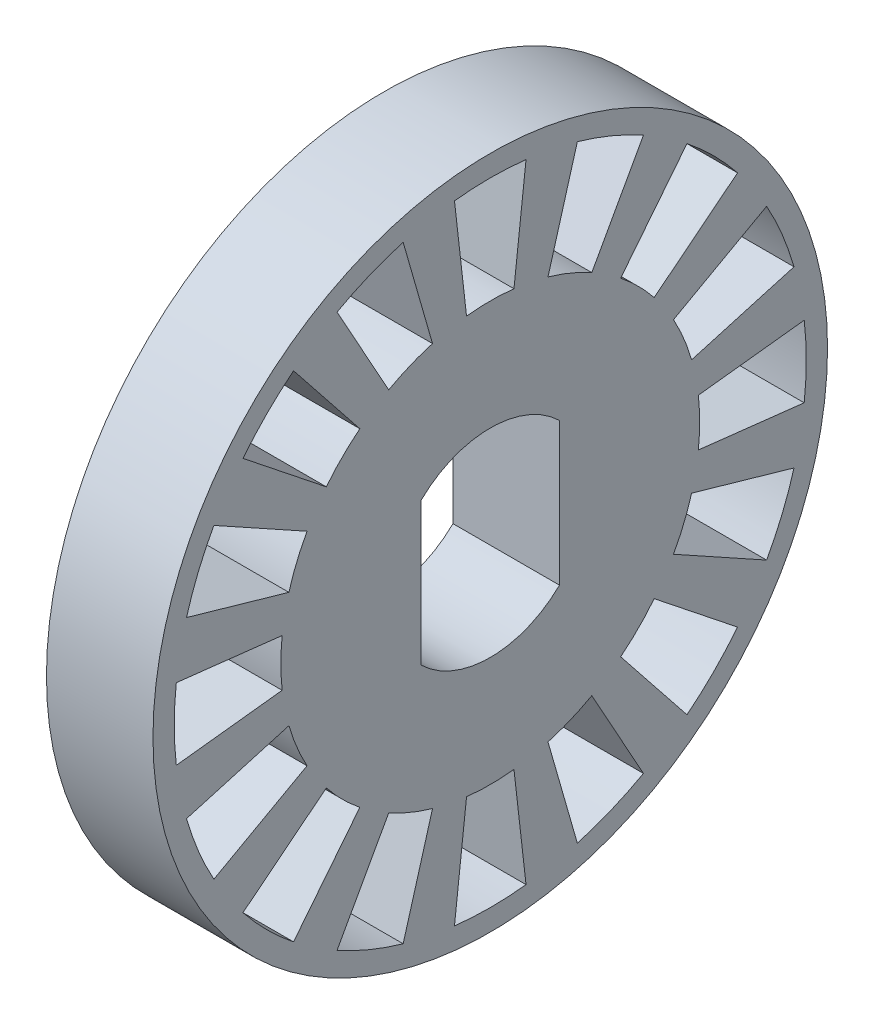
SolidWorks part; units mm, degrees
ref_plane "Front Plane" through (0, 0, 0) normal (0, 0, 1) x (1, 0, 0)
ref_plane "Top Plane" through (0, 0, 0) normal (0, 1, 0) x (1, 0, 0)
ref_plane "Right Plane" through (0, 0, 0) normal (1, 0, 0) x (0, 0, -1)
sketch "Sketch1" plane through (0, 0, 0) normal (1, 0, 0) x (0, 0, -1)
  line L1 (-1.95, -2.0094) -> (1.95, -2.0094) construction
  line L2 (-1.95, -2.0094) -> (-1.95, 2.0094)
  line L3 (-1.95, 2.0094) -> (1.95, 2.0094) construction
  line L4 (1.95, -2.0094) -> (1.95, 2.0094)
  line L5 (-1.95, -2.0094) -> (1.95, 2.0094) construction
  line L6 (-1.95, 2.0094) -> (1.95, -2.0094) construction
  circle A0 centre (0, 0) radius 9.5
  circle A1 centre (0, 0) radius 2.8
  dimension "D1" = 19
  dimension "D2" = 5.6
  dimension "D3" = 3.9
extrude "Boss-Extrude1" add sketch "Sketch1" along normal blind 3 contours A0 A1 | L4 A1 | L2 A1
sketch "Sketch2" [suppressed] plane through (3, 0, 0) normal (1, 0, 0) x (0, 0, -1)
  line L0 (0, 0) -> (0, 9.5) construction
  line L1 (2.8313, 6.1249) -> (3.4493, 8.027)
  line L2 (-0.8, 6.7) -> (0.8, 6.7)
  line L3 (-0.8, 6.7) -> (-0.8, 8.7)
  line L4 (-0.8, 8.7) -> (0.8, 8.7)
  line L5 (0.8, 6.7) -> (0.8, 8.7)
  line L6 (-0.8, 6.7) -> (0.8, 8.7) construction
  line L7 (-0.8, 8.7) -> (0.8, 6.7) construction
  line L8 (1.9276, 8.5214) -> (3.4493, 8.027)
  line L9 (1.3096, 6.6193) -> (1.9276, 8.5214)
  line L10 (1.3096, 6.6193) -> (2.8313, 6.1249)
  line L11 (4.5854, 4.9502) -> (5.7609, 6.5682)
  line L12 (4.4665, 7.5087) -> (5.7609, 6.5682)
  line L13 (3.2909, 5.8906) -> (4.4665, 7.5087)
  line L14 (3.2909, 5.8906) -> (4.5854, 4.9502)
  line L15 (5.8906, 3.2909) -> (7.5087, 4.4665)
  line L16 (6.5682, 5.7609) -> (7.5087, 4.4665)
  line L17 (4.9502, 4.5854) -> (6.5682, 5.7609)
  line L18 (4.9502, 4.5854) -> (5.8906, 3.2909)
  line L19 (6.6193, 1.3096) -> (8.5214, 1.9276)
  line L20 (8.027, 3.4493) -> (8.5214, 1.9276)
  line L21 (6.1249, 2.8313) -> (8.027, 3.4493)
  line L22 (6.1249, 2.8313) -> (6.6193, 1.3096)
  line L23 (6.7, -0.8) -> (8.7, -0.8)
  line L24 (8.7, 0.8) -> (8.7, -0.8)
  line L25 (6.7, 0.8) -> (8.7, 0.8)
  line L26 (6.7, 0.8) -> (6.7, -0.8)
  line L27 (6.1249, -2.8313) -> (8.027, -3.4493)
  line L28 (8.5214, -1.9276) -> (8.027, -3.4493)
  line L29 (6.6193, -1.3096) -> (8.5214, -1.9276)
  line L30 (6.6193, -1.3096) -> (6.1249, -2.8313)
  line L31 (4.9502, -4.5854) -> (6.5682, -5.7609)
  line L32 (7.5087, -4.4665) -> (6.5682, -5.7609)
  line L33 (5.8906, -3.2909) -> (7.5087, -4.4665)
  line L34 (5.8906, -3.2909) -> (4.9502, -4.5854)
  line L35 (3.2909, -5.8906) -> (4.4665, -7.5087)
  line L36 (5.7609, -6.5682) -> (4.4665, -7.5087)
  line L37 (4.5854, -4.9502) -> (5.7609, -6.5682)
  line L38 (4.5854, -4.9502) -> (3.2909, -5.8906)
  line L39 (1.3096, -6.6193) -> (1.9276, -8.5214)
  line L40 (3.4493, -8.027) -> (1.9276, -8.5214)
  line L41 (2.8313, -6.1249) -> (3.4493, -8.027)
  line L42 (2.8313, -6.1249) -> (1.3096, -6.6193)
  line L43 (-0.8, -6.7) -> (-0.8, -8.7)
  line L44 (0.8, -8.7) -> (-0.8, -8.7)
  line L45 (0.8, -6.7) -> (0.8, -8.7)
  line L46 (0.8, -6.7) -> (-0.8, -6.7)
  line L47 (-2.8313, -6.1249) -> (-3.4493, -8.027)
  line L48 (-1.9276, -8.5214) -> (-3.4493, -8.027)
  line L49 (-1.3096, -6.6193) -> (-1.9276, -8.5214)
  line L50 (-1.3096, -6.6193) -> (-2.8313, -6.1249)
  line L51 (-4.5854, -4.9502) -> (-5.7609, -6.5682)
  line L52 (-4.4665, -7.5087) -> (-5.7609, -6.5682)
  line L53 (-3.2909, -5.8906) -> (-4.4665, -7.5087)
  line L54 (-3.2909, -5.8906) -> (-4.5854, -4.9502)
  line L55 (-5.8906, -3.2909) -> (-7.5087, -4.4665)
  line L56 (-6.5682, -5.7609) -> (-7.5087, -4.4665)
  line L57 (-4.9502, -4.5854) -> (-6.5682, -5.7609)
  line L58 (-4.9502, -4.5854) -> (-5.8906, -3.2909)
  line L59 (-6.6193, -1.3096) -> (-8.5214, -1.9276)
  line L60 (-8.027, -3.4493) -> (-8.5214, -1.9276)
  line L61 (-6.1249, -2.8313) -> (-8.027, -3.4493)
  line L62 (-6.1249, -2.8313) -> (-6.6193, -1.3096)
  line L63 (-6.7, 0.8) -> (-8.7, 0.8)
  line L64 (-8.7, -0.8) -> (-8.7, 0.8)
  line L65 (-6.7, -0.8) -> (-8.7, -0.8)
  line L66 (-6.7, -0.8) -> (-6.7, 0.8)
  line L67 (-6.1249, 2.8313) -> (-8.027, 3.4493)
  line L68 (-8.5214, 1.9276) -> (-8.027, 3.4493)
  line L69 (-6.6193, 1.3096) -> (-8.5214, 1.9276)
  line L70 (-6.6193, 1.3096) -> (-6.1249, 2.8313)
  line L71 (-4.9502, 4.5854) -> (-6.5682, 5.7609)
  line L72 (-7.5087, 4.4665) -> (-6.5682, 5.7609)
  line L73 (-5.8906, 3.2909) -> (-7.5087, 4.4665)
  line L74 (-5.8906, 3.2909) -> (-4.9502, 4.5854)
  line L75 (-3.2909, 5.8906) -> (-4.4665, 7.5087)
  line L76 (-5.7609, 6.5682) -> (-4.4665, 7.5087)
  line L77 (-4.5854, 4.9502) -> (-5.7609, 6.5682)
  line L78 (-4.5854, 4.9502) -> (-3.2909, 5.8906)
  line L79 (-1.3096, 6.6193) -> (-1.9276, 8.5214)
  line L80 (-3.4493, 8.027) -> (-1.9276, 8.5214)
  line L81 (-2.8313, 6.1249) -> (-3.4493, 8.027)
  line L82 (-2.8313, 6.1249) -> (-1.3096, 6.6193)
  circle A0 centre (0, 0) radius 9.5 construction
  circle A1 centre (0, 0) radius 6.7476 construction
  point P5 (0, 7.7)
  point P10 (0, 0)
  point P88 (0, 0)
  point P89 (5.5589, 7.5577)
  point P90 (0, 0)
  dimension "D1" = 1.6
  dimension "D2" = 0.8
  dimension "D3" = 2
  dimension "D5" = 0.5159
  dimension "D4" = 20
extrude "Cut-Extrude1" [suppressed] cut sketch "Sketch2" against normal through all
sketch "Sketch3" plane through (3, 0, 0) normal (1, 0, 0) x (0, 0, -1)
  line L0 (0, 0) -> (0, 9.5) construction
  line L1 (0, 0) -> (1.0754, 9.4389) construction
  line L2 (0, 0) -> (-1.0754, 9.4389) construction
  line L3 (-1.0754, 9.4389) -> (0, 4.75) construction
  line L4 (0, 4.75) -> (1.0754, 9.4389) construction
  line L5 (-0.6679, 5.8621) -> (-1.0075, 8.8428)
  line L6 (0.6679, 5.8621) -> (1.0075, 8.8428)
  circle A0 centre (0, 0) radius 9.5 construction
  circle A1 centre (0, 0) radius 8.9
  circle A2 centre (0, 0) radius 5.9
  dimension "D2" = 0.6
  dimension "D3" = 3
  dimension "D1" = 13
  dimension "D4" = 2.015
  dimension "D5" = 1.3358
extrude "Cut-Extrude2" cut sketch "Sketch3" against normal blind 3 contours A2 L6 A1 L5
pattern_circular "CirPattern1" count 16 over 360 about axis through (0, 0, 0) along (1, 0, 0) of "Cut-Extrude2"
